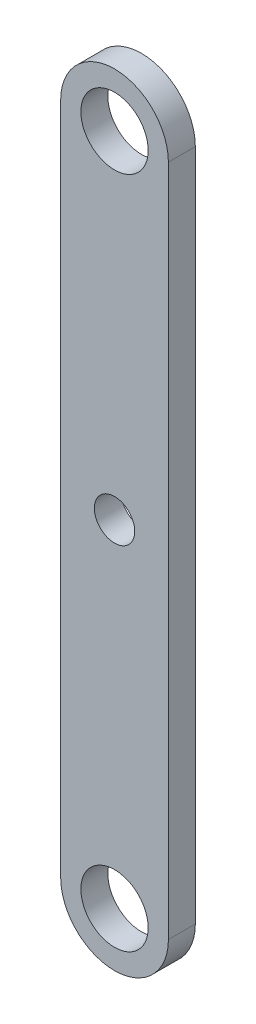
SolidWorks part; units mm, degrees
ref_plane "Front Plane" through (0, 0, 0) normal (0, 0, 1) x (1, 0, 0)
ref_plane "Top Plane" through (0, 0, 0) normal (0, 1, 0) x (1, 0, 0)
ref_plane "Right Plane" through (0, 0, 0) normal (1, 0, 0) x (0, 0, -1)
sketch "Sketch1" plane through (0, 0, 0) normal (0, 0, 1) x (1, 0, 0)
  line L0 (-20, 0) -> (-20, 250)
  line L1 (20, 0) -> (20, 250)
  arc A0 (-20, 0) -> (20, 0) centre (0, 0) ccw
  arc A1 (20, 250) -> (-20, 250) centre (0, 250) ccw
  dimension "D1" = 40
  dimension "D2" = 250
extrude "Boss-Extrude1" add sketch "Sketch1" along normal blind 10
sketch "Sketch2" plane through (0, 0, 0) normal (0, 0, -1) x (-1, 0, 0)
  circle A0 centre (0, 0) radius 12.5
  circle A1 centre (0, 250) radius 12.5
  dimension "D1" = 25
extrude "Cut-Extrude1" cut sketch "Sketch2" against normal through all
sketch "Sketch3" plane through (0, 0, 0) normal (0, 0, -1) x (-1, 0, 0)
  circle A0 centre (0, 125) radius 7.5
  dimension "D1" = 15
extrude "Cut-Extrude2" cut sketch "Sketch3" against normal blind 10
